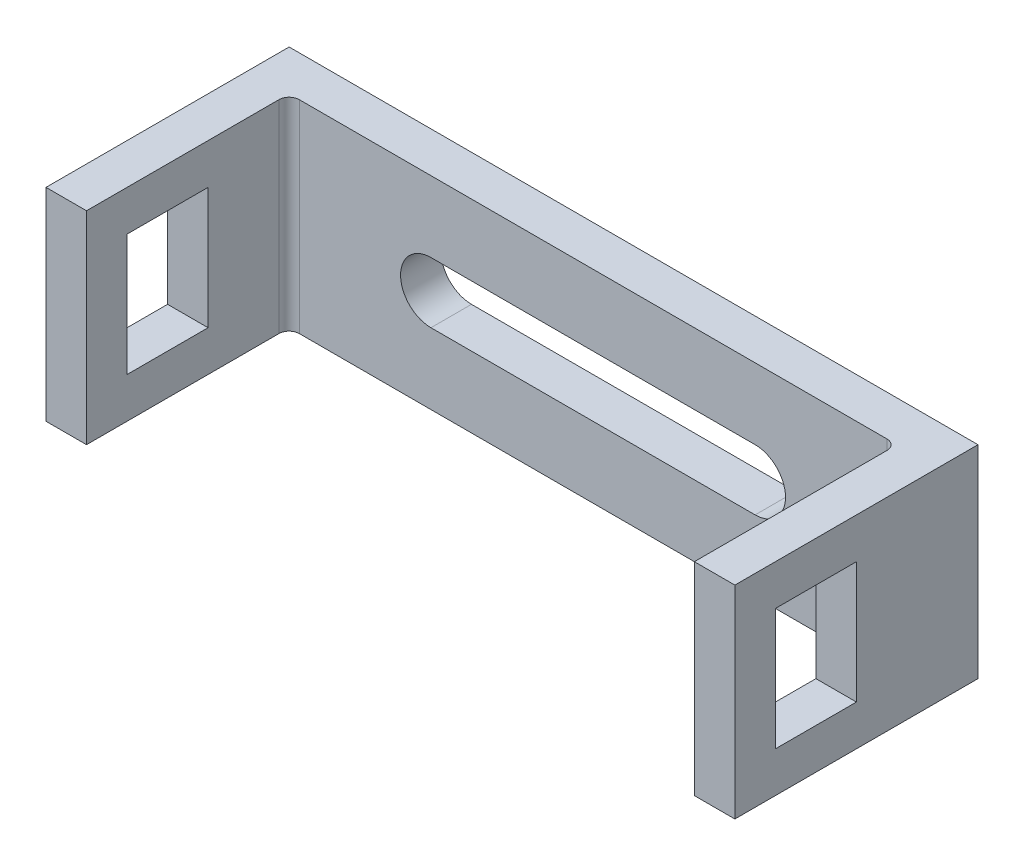
SolidWorks part; units mm, degrees
ref_plane "Front Plane" through (0, 0, 0) normal (0, 0, 1) x (1, 0, 0)
ref_plane "Top Plane" through (0, 0, 0) normal (0, 1, 0) x (1, 0, 0)
ref_plane "Right Plane" through (0, 0, 0) normal (1, 0, 0) x (0, 0, -1)
sketch "Sketch1" plane through (0, 0, 0) normal (0, 0, 1) x (1, 0, 0)
  line L1 (-17, 5) -> (17, 5)
  line L2 (-17, 5) -> (-17, -5)
  line L3 (-17, -5) -> (17, -5)
  line L4 (17, 5) -> (17, -5)
  line L5 (-17, 5) -> (17, -5) construction
  line L6 (-17, -5) -> (17, 5) construction
  point P0 (0, 0)
  dimension "D1" = 34
  dimension "D2" = 10
extrude "Boss-Extrude1" add sketch "Sketch1" along normal blind 2
sketch "Sketch2" plane through (0, 0, 2) normal (0, 0, 1) x (1, 0, 0)
  line L0 (-17, -5) -> (17, -5) construction
  line L1 (-17, 5) -> (-15, 5)
  line L2 (-17, 5) -> (-17, -5)
  line L3 (-17, -5) -> (-15, -5)
  line L4 (-15, 5) -> (-15, -5)
  line L6 (17, 5) -> (15, 5)
  line L7 (17, 5) -> (17, -5)
  line L8 (17, -5) -> (15, -5)
  line L9 (15, 5) -> (15, -5)
  dimension "D1" = 2
  dimension "D2" = 2
extrude "Boss-Extrude2" add sketch "Sketch2" along normal blind 10
fillet "Fillet1" radius 0.5 2 edges at (15, 0, 2) (-15, 0, 2)
sketch "Sketch3" plane through (17, 0, 0) normal (1, 0, 0) x (0, 0, -1)
  line L0 (0, -5) -> (0, 5) construction
  line L1 (-10, 3) -> (-6, 3)
  line L2 (-10, 3) -> (-10, -3)
  line L3 (-10, -3) -> (-6, -3)
  line L4 (-6, 3) -> (-6, -3)
  point P6 (-10, 0)
  dimension "D1" = 6
  dimension "D2" = 4
  dimension "D3" = 6
extrude "Cut-Extrude1" cut sketch "Sketch3" against normal through all both and the other way through all
sketch "Sketch4" plane through (0, 0, 0) normal (0, 0, -1) x (-1, 0, 0)
  line L0 (-8, 0) -> (8, 0) construction
  line L1 (-8, -1.5) -> (8, -1.5)
  line L2 (-8, 1.5) -> (8, 1.5)
  arc A0 (-8, 1.5) -> (-8, -1.5) centre (-8, 0) ccw
  arc A1 (8, -1.5) -> (8, 1.5) centre (8, 0) ccw
  point P3 (0, 0)
  point P4 (0, 0)
  dimension "D2" = 3
  dimension "D3" = 3
  dimension "D1" = 16
  dimension "D4" = 16
extrude "Cut-Extrude2" cut sketch "Sketch4" against normal through all both and the other way through all
